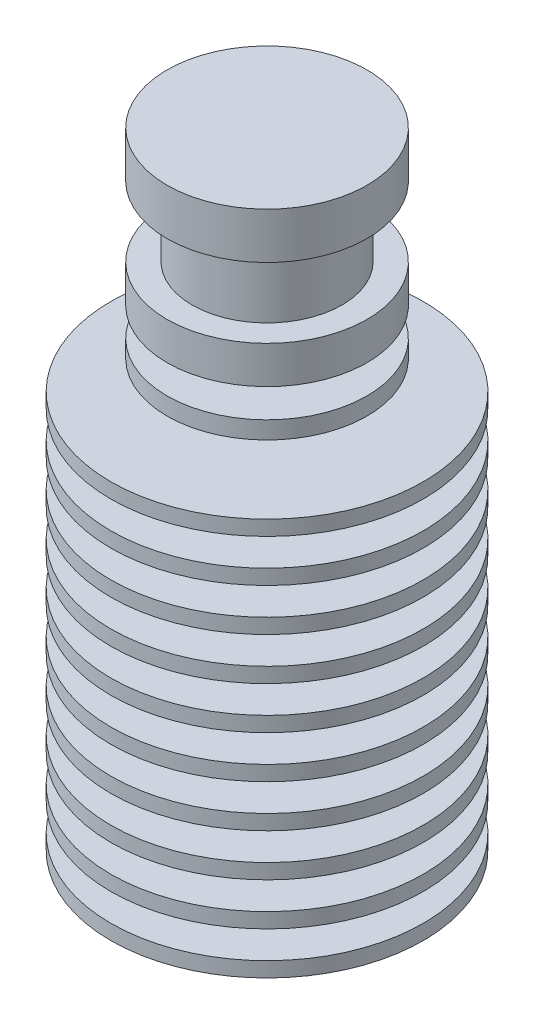
SolidWorks part; units mm, degrees
material "6061 Alloy"
ref_plane "Front Plane" through (0, 0, 0) normal (0, 0, 1) x (1, 0, 0)
ref_plane "Top Plane" through (0, 0, 0) normal (0, 1, 0) x (1, 0, 0)
ref_plane "Right Plane" through (0, 0, 0) normal (1, 0, 0) x (0, 0, -1)
sketch "Sketch1" plane through (0, 0, 0) normal (0, 0, 1) x (1, 0, 0)
  line L0 (0, 0) -> (0, -101.2298) construction
  line L1 (0, 0) -> (8, 0)
  line L2 (8, 0) -> (8, -3.7)
  line L3 (8, -3.7) -> (6, -3.7)
  line L4 (6, -3.7) -> (6, -9.3)
  line L5 (6, -9.3) -> (8, -9.3)
  line L6 (8, -9.3) -> (8, -12.3)
  line L7 (8, -12.3) -> (4.5, -12.3)
  line L8 (4.5, -12.3) -> (4.5, -14.6)
  line L9 (4.5, -18.3) -> (12.5, -18.3)
  line L10 (12.5, -18.3) -> (12.5, -50.1)
  line L11 (12.5, -50.1) -> (0, -50.1)
  line L12 (0, -50.1) -> (0, 0)
  line L13 (4.5, -14.6) -> (8, -14.6)
  line L14 (8, -14.6) -> (8, -16)
  line L15 (8, -16) -> (4.5, -16)
  line L16 (4.5, -16) -> (4.5, -18.3)
  dimension "D1" = 16
  dimension "D2" = 12
  dimension "D3" = 9
  dimension "D4" = 3.7
  dimension "D5" = 9.3
  dimension "D6" = 12.3
  dimension "D7" = 14.6
  dimension "D8" = 18.3
  dimension "D9" = 31.8
  dimension "D10" = 25
revolve "Revolve1" add sketch "Sketch1" angle 360 about L0
sketch "Sketch2" plane through (0, 0, 0) normal (0, 0, 1) x (1, 0, 0)
  line L0 (0, 0) -> (0, -50.1) construction
  line L1 (-12.5, -50.1) -> (12.5, -50.1) construction
  line L2 (4.5, -48.9) -> (12.5, -48.9)
  line L3 (12.5, -50.1) -> (12.5, -18.3) construction
  line L4 (12.5, -48.9) -> (12.5, -46.7)
  line L5 (12.5, -46.7) -> (4.5, -46.7)
  line L6 (4.5, -46.7) -> (4.5, -48.9)
  dimension "D1" = 2.2
  dimension "D2" = 3.4
  dimension "D3" = 9
revolve "Cut-Revolve3" cut sketch "Sketch2" angle 360 about L0
pattern_linear "LPattern1" count 9 spacing 3.4 along (0, 1, 0) of "Cut-Revolve3"
sketch "Sketch3" plane through (0, -50.1, 0) normal (0, -1, 0) x (1, 0, 0)
  circle A0 centre (0, 0) radius 7.5
  dimension "D1" = 15
extrude "Boss-Extrude1" add sketch "Sketch3" against normal up to surface (18.2 mm away) up to face at (0, -31.9, 12.5)
sketch "Sketch4" plane through (0, -31.9, 0) normal (0, 1, 0) x (1, 0, 0)
  circle A0 centre (0, 0) radius 6
  dimension "D1" = 12
extrude "Boss-Extrude2" add sketch "Sketch4" along normal up to surface (2.2 mm away) up to face at (0, -29.7, 4.5)
